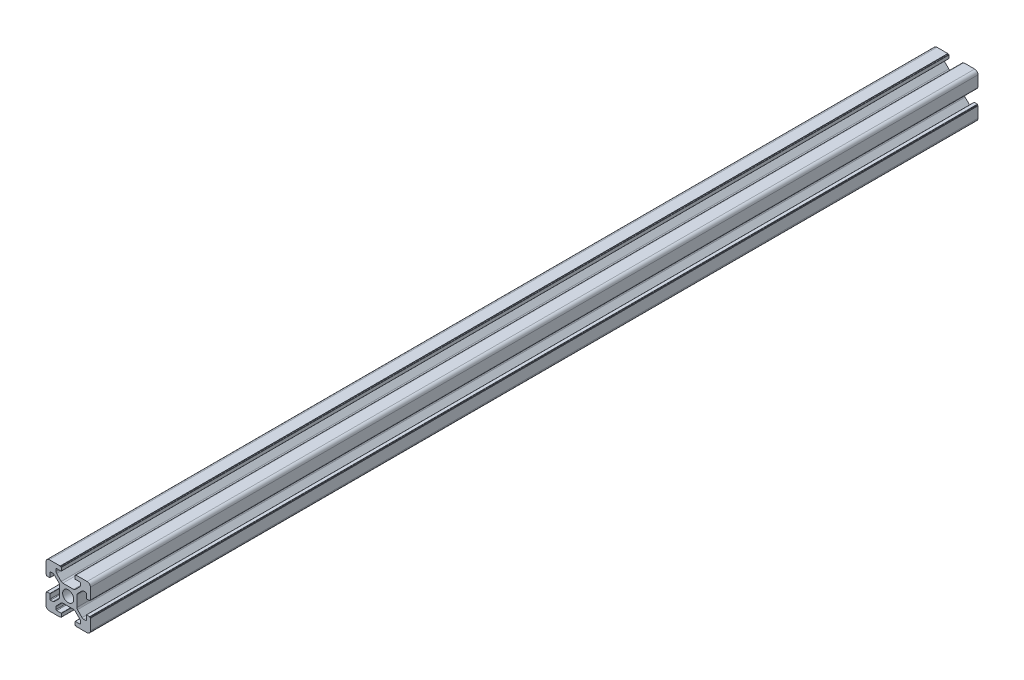
SolidWorks part; units mm, degrees
material "6063-T5"
ref_plane "前视基准面" through (0, 0, 0) normal (0, 0, 1) x (1, 0, 0)
ref_plane "上视基准面" through (0, 0, 0) normal (0, 1, 0) x (1, 0, 0)
ref_plane "右视基准面" through (0, 0, 0) normal (1, 0, 0) x (0, 0, -1)
sketch "草图1" plane through (0, 0, 0) normal (0, 0, 1) x (1, 0, 0)
  line L0 (-1.4389, 10) -> (24.3741, 10) construction
  line L1 (20, 13.6) -> (20, 20)
  line L2 (0, 0) -> (0, 6.4)
  line L3 (0, 20) -> (6.4, 20)
  line L4 (20, 0) -> (20, 6.4)
  line L5 (10, 21.5388) -> (10, -2.4017) construction
  line L6 (6.9, 18.3) -> (6.9, 19.7)
  line L7 (6.8, 18.2) -> (4.8, 18.2)
  line L8 (4.5, 17.9) -> (4.5, 16.9749)
  line L9 (4.7929, 16.2678) -> (6.8678, 14.1929)
  line L10 (7.5749, 13.9) -> (12.4251, 13.9)
  line L11 (6.8, 19.8) -> (6.4, 19.8)
  line L12 (6.4, 19.8) -> (6.4, 20)
  line L13 (0, 13.6) -> (0.2, 13.6)
  line L14 (0.2, 13.6) -> (0.2, 13.2)
  line L15 (0.3, 13.1) -> (1.7, 13.1)
  line L16 (1.8, 13.2) -> (1.8, 15.2)
  line L17 (2.1, 15.5) -> (3.0251, 15.5)
  line L18 (3.7322, 15.2071) -> (5.8071, 13.1322)
  line L19 (6.1, 12.4251) -> (6.1, 7.5749)
  line L20 (13.6, 19.8) -> (13.6, 20)
  line L21 (13.2, 19.8) -> (13.6, 19.8)
  line L22 (13.1, 18.3) -> (13.1, 19.7)
  line L23 (13.2, 18.2) -> (15.2, 18.2)
  line L24 (15.5, 17.9) -> (15.5, 16.9749)
  line L25 (15.2071, 16.2678) -> (13.1322, 14.1929)
  line L26 (0, 6.4) -> (0.2, 6.4)
  line L27 (0.2, 6.4) -> (0.2, 6.8)
  line L28 (0.3, 6.9) -> (1.7, 6.9)
  line L29 (1.8, 6.8) -> (1.8, 4.8)
  line L30 (2.1, 4.5) -> (3.0251, 4.5)
  line L31 (3.7322, 4.7929) -> (5.8071, 6.8678)
  line L32 (13.6, 20) -> (20, 20)
  line L33 (0, 13.6) -> (0, 20)
  line L34 (13.6, 0.2) -> (13.6, 0)
  line L35 (13.2, 0.2) -> (13.6, 0.2)
  line L36 (13.1, 1.7) -> (13.1, 0.3)
  line L37 (13.2, 1.8) -> (15.2, 1.8)
  line L38 (15.5, 2.1) -> (15.5, 3.0251)
  line L39 (15.2071, 3.7322) -> (13.1322, 5.8071)
  line L40 (4.5, 2.1) -> (4.5, 3.0251)
  line L41 (6.8, 1.8) -> (4.8, 1.8)
  line L42 (6.4, 0.2) -> (6.4, 0)
  line L43 (6.8, 0.2) -> (6.4, 0.2)
  line L44 (6.9, 1.7) -> (6.9, 0.3)
  line L45 (4.7929, 3.7322) -> (6.8678, 5.8071)
  line L46 (7.5749, 6.1) -> (12.4251, 6.1)
  line L47 (20, 6.4) -> (19.8, 6.4)
  line L48 (19.8, 6.4) -> (19.8, 6.8)
  line L49 (19.7, 6.9) -> (18.3, 6.9)
  line L50 (18.2, 6.8) -> (18.2, 4.8)
  line L51 (17.9, 4.5) -> (16.9749, 4.5)
  line L52 (16.2678, 4.7929) -> (14.1929, 6.8678)
  line L53 (13.9, 12.4251) -> (13.9, 7.5749)
  line L54 (16.2678, 15.2071) -> (14.1929, 13.1322)
  line L55 (17.9, 15.5) -> (16.9749, 15.5)
  line L56 (18.2, 13.2) -> (18.2, 15.2)
  line L57 (19.7, 13.1) -> (18.3, 13.1)
  line L58 (19.8, 13.6) -> (19.8, 13.2)
  line L59 (20, 13.6) -> (19.8, 13.6)
  line L60 (0, 0) -> (6.4, 0)
  line L61 (13.6, 0) -> (20, 0)
  arc A0 (6.1, 12.4251) -> (5.8071, 13.1322) centre (5.1, 12.4251) ccw
  arc A1 (7.5749, 13.9) -> (6.8678, 14.1929) centre (7.5749, 14.9) cw
  arc A2 (4.5, 16.9749) -> (4.7929, 16.2678) centre (5.5, 16.9749) ccw
  arc A3 (3.7322, 15.2071) -> (3.0251, 15.5) centre (3.0251, 14.5) ccw
  arc A4 (4.5, 17.9) -> (4.8, 18.2) centre (4.8, 17.9) cw
  arc A5 (1.8, 15.2) -> (2.1, 15.5) centre (2.1, 15.2) cw
  arc A6 (0.3, 13.1) -> (0.2, 13.2) centre (0.3, 13.2) cw
  arc A7 (6.9, 19.7) -> (6.8, 19.8) centre (6.8, 19.7) ccw
  arc A8 (1.7, 13.1) -> (1.8, 13.2) centre (1.7, 13.2) ccw
  arc A9 (6.9, 18.3) -> (6.8, 18.2) centre (6.8, 18.3) cw
  arc A10 (13.1, 19.7) -> (13.2, 19.8) centre (13.2, 19.7) cw
  arc A11 (13.1, 18.3) -> (13.2, 18.2) centre (13.2, 18.3) ccw
  arc A12 (15.5, 17.9) -> (15.2, 18.2) centre (15.2, 17.9) ccw
  arc A13 (15.5, 16.9749) -> (15.2071, 16.2678) centre (14.5, 16.9749) cw
  arc A14 (12.4251, 13.9) -> (13.1322, 14.1929) centre (12.4251, 14.9) ccw
  arc A15 (0.3, 6.9) -> (0.2, 6.8) centre (0.3, 6.8) ccw
  arc A16 (1.7, 6.9) -> (1.8, 6.8) centre (1.7, 6.8) cw
  arc A17 (1.8, 4.8) -> (2.1, 4.5) centre (2.1, 4.8) ccw
  arc A18 (3.7322, 4.7929) -> (3.0251, 4.5) centre (3.0251, 5.5) cw
  arc A19 (6.1, 7.5749) -> (5.8071, 6.8678) centre (5.1, 7.5749) cw
  arc A20 (13.1, 0.3) -> (13.2, 0.2) centre (13.2, 0.3) ccw
  arc A21 (13.1, 1.7) -> (13.2, 1.8) centre (13.2, 1.7) cw
  arc A22 (15.5, 2.1) -> (15.2, 1.8) centre (15.2, 2.1) cw
  arc A23 (15.5, 3.0251) -> (15.2071, 3.7322) centre (14.5, 3.0251) ccw
  arc A24 (12.4251, 6.1) -> (13.1322, 5.8071) centre (12.4251, 5.1) cw
  arc A25 (4.5, 2.1) -> (4.8, 1.8) centre (4.8, 2.1) ccw
  arc A26 (6.9, 0.3) -> (6.8, 0.2) centre (6.8, 0.3) cw
  arc A27 (6.9, 1.7) -> (6.8, 1.8) centre (6.8, 1.7) ccw
  arc A28 (4.5, 3.0251) -> (4.7929, 3.7322) centre (5.5, 3.0251) cw
  arc A29 (7.5749, 6.1) -> (6.8678, 5.8071) centre (7.5749, 5.1) ccw
  arc A30 (19.7, 6.9) -> (19.8, 6.8) centre (19.7, 6.8) cw
  arc A31 (18.3, 6.9) -> (18.2, 6.8) centre (18.3, 6.8) ccw
  arc A32 (18.2, 4.8) -> (17.9, 4.5) centre (17.9, 4.8) cw
  arc A33 (16.2678, 4.7929) -> (16.9749, 4.5) centre (16.9749, 5.5) ccw
  arc A34 (13.9, 7.5749) -> (14.1929, 6.8678) centre (14.9, 7.5749) ccw
  arc A35 (13.9, 12.4251) -> (14.1929, 13.1322) centre (14.9, 12.4251) cw
  arc A36 (16.2678, 15.2071) -> (16.9749, 15.5) centre (16.9749, 14.5) cw
  arc A37 (18.2, 15.2) -> (17.9, 15.5) centre (17.9, 15.2) ccw
  arc A38 (18.3, 13.1) -> (18.2, 13.2) centre (18.3, 13.2) cw
  arc A39 (19.7, 13.1) -> (19.8, 13.2) centre (19.7, 13.2) ccw
  circle A40 centre (10, 10) radius 2.5
  point P39 (0.2, 13.1)
  point P42 (6.9, 19.8)
  point P45 (1.8, 13.1)
  point P48 (6.9, 18.2)
  point P66 (10, 13.9)
  point P83 (6.1, 10)
  dimension "D19" = 1
  dimension "D20" = 1
  dimension "D21" = 0.3
  dimension "D22" = 0.1
  dimension "D23" = 5
  dimension "D1" = 20
  dimension "D2" = 20
  dimension "D3" = 10
  dimension "D4" = 10
  dimension "D5" = 1.8
  dimension "D6" = 0.5
  dimension "D7" = 1.6
  dimension "D8" = 3.1
  dimension "D9" = 6.1
  dimension "D10" = 5.5
  dimension "D11" = 3.1
  dimension "D12" = 6.1
  dimension "D13" = 5.5
  dimension "D14" = 1.8
  dimension "D15" = 0.5
  dimension "D16" = 1.5
  dimension "D17" = 45
  dimension "D18" = 1.6
extrude "凸台-拉伸1" add sketch "草图1" along normal blind 400
fillet "圆角1" radius 1.5 4 edges at (20, 0, 200) (0, 0, 200) (0, 20, 200) (20, 20, 200)
